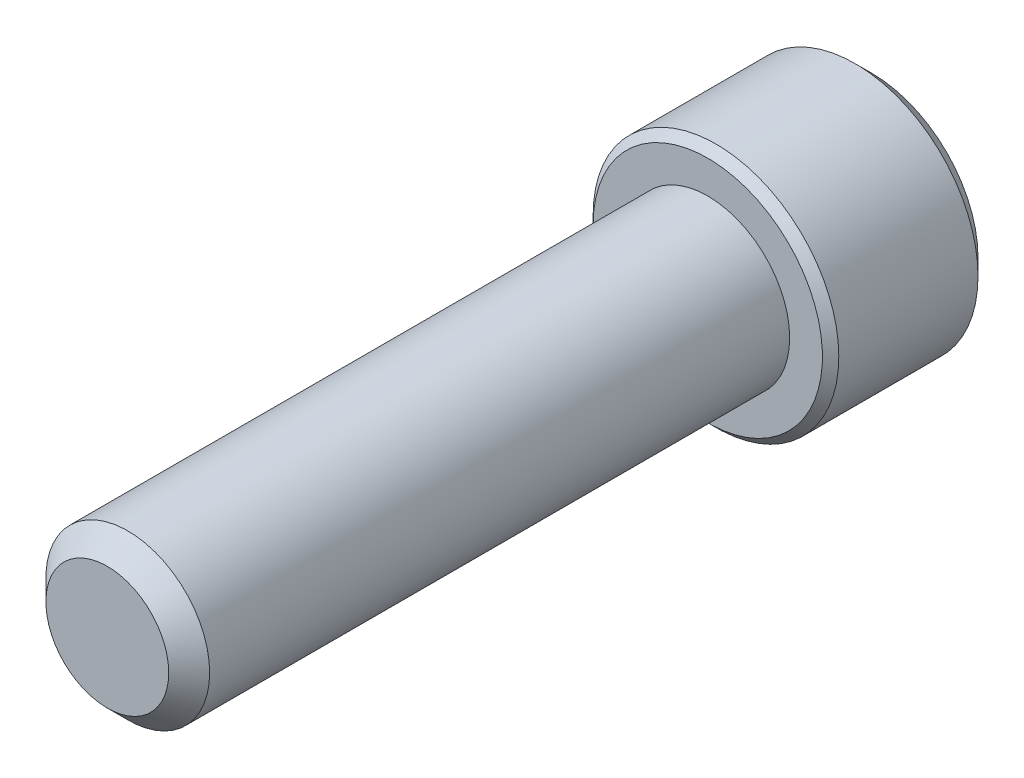
SolidWorks part; units mm, degrees
ref_plane "Front Plane" through (0, 0, 0) normal (0, 0, 1) x (1, 0, 0)
ref_plane "Top Plane" through (0, 0, 0) normal (0, 1, 0) x (1, 0, 0)
ref_plane "Right Plane" through (0, 0, 0) normal (1, 0, 0) x (0, 0, -1)
sketch "Sketch1" plane through (0, 0, 0) normal (0, 0, 1) x (1, 0, 0)
  line L0 (0, 4.7625) -> (0, -4.7625) construction
  circle A0 centre (0, 0) radius 4.7625
  dimension "OD" = 9.525
extrude "Extrude1" add sketch "Sketch1" against normal blind 34.925
sketch "Sketch6" plane through (0, 0, -34.925) normal (0, 0, -1) x (-1, 0, 0)
  circle A0 centre (0, 0) radius 7.1438
  dimension "head dia" = 14.2875
extrude "Extrude2" add sketch "Sketch6" along normal blind 9.525
sketch "Sketch7" plane through (0, 0, -44.45) normal (0, 0, -1) x (-1, 0, 0)
  line L1 (0, 4.5827) -> (-3.9688, 2.2914)
  line L2 (-3.9688, 2.2914) -> (-3.9688, -2.2914)
  line L3 (-3.9688, -2.2914) -> (0, -4.5827)
  line L4 (0, -4.5827) -> (3.9688, -2.2914)
  line L5 (3.9688, -2.2914) -> (3.9687, 2.2914)
  line L6 (3.9687, 2.2914) -> (0, 4.5827)
  circle A0 centre (0, 0) radius 3.9688 construction
  dimension "hex dia" = 7.9375
extrude "Cut-Extrude1" cut sketch "Sketch7" against normal blind 5.9531
sketch "Sketch8" plane through (0, 0, -44.45) normal (0, 0, -1) x (-1, 0, 0)
  circle A0 centre (0, 0) radius 4.5827
extrude "Cut-Extrude2" cut sketch "Sketch8" against normal blind 0.9525 draft 45
chamfer "Chamfer1" distance 0.9525 angle 45 1 edges at (-7.1438, 0, -44.45)
chamfer "Chamfer2" distance 0.4763 angle 45 1 edges at (-7.1438, 0, -34.925)
chamfer "Chamfer3" distance 1.1906 angle 45 1 edges at (4.7625, 0, 0)
